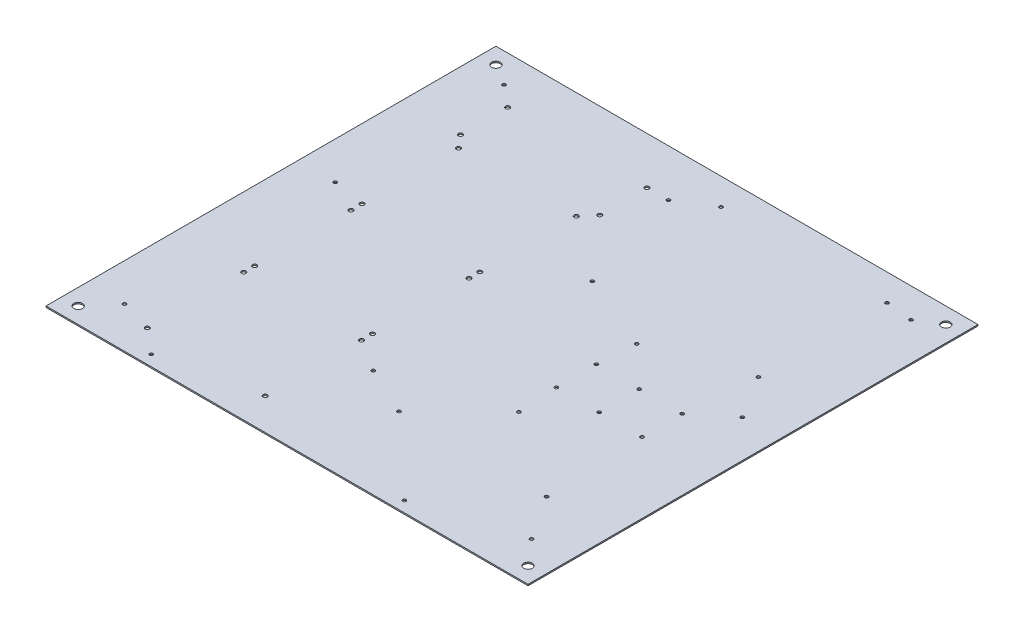
SolidWorks part; units mm, degrees
ref_plane "Front Plane" through (0, 0, 0) normal (0, 0, 1) x (1, 0, 0)
ref_plane "Top Plane" through (0, 0, 0) normal (0, 1, 0) x (1, 0, 0)
ref_plane "Right Plane" through (0, 0, 0) normal (1, 0, 0) x (0, 0, -1)
sketch "Sketch1" plane through (0, 0, 0) normal (0, 1, 0) x (1, 0, 0)
  line L1 (0, 0) -> (571.5, 0)
  line L2 (0, 0) -> (0, 533.4)
  line L3 (0, 533.4) -> (571.5, 533.4)
  line L4 (571.5, 0) -> (571.5, 533.4)
  dimension "D1" = 533.4
  dimension "D2" = 571.5
extrude "Boss-Extrude1" add sketch "Sketch1" along normal blind 1.5875
hole_wizard "#10-32 Tapped Hole1" positions "Sketch3" profile "Sketch2" tap size "#10-32" standard "ANSI Inch" end condition through all
sketch "Sketch3" plane through (0, 1.5875, 0) normal (0, 1, 0) x (1, 0, 0)
  line L0 (571.5, 533.4) -> (0, 533.4) construction
  line L1 (0, 533.4) -> (0, 0) construction
  point P0 (298.45, 501.65)
  point P2 (495.3, 501.65)
  point P4 (298.45, 349.25)
  point P6 (495.3, 349.25)
  dimension "D1" = 196.85
  dimension "D2" = 152.4
  dimension "D3" = 31.75
  dimension "D4" = 298.45
sketch "Sketch2" plane through (298.45, 1.5875, -501.65) normal (1, 0, 0) x (0, 0, 1)
  line L0 (0, 0) -> (0, 1.5875)
  line L1 (0, 1.5875) -> (2.0193, 1.5875)
  line L2 (2.0193, 1.5875) -> (2.0193, 0)
  line L5 (2.0193, 0) -> (0, 0)
  line L11 (0, -6.35) -> (0, 107.95) construction
  dimension "Thru Tap Drill Dia." = 4.0386
  dimension "Thru Tap Drill Depth" = 1.5875
cosmetic thread "Hole Thread1" parameters "D2"=4.826
cosmetic thread "Hole Thread2" parameters "D2"=4.826
cosmetic thread "Hole Thread3" parameters "D2"=4.826
cosmetic thread "Hole Thread4" parameters "D2"=4.826
hole_wizard "1/4-20 Tapped Hole1" positions "Sketch4" profile "Sketch5" tap size "1/4-20" standard "ANSI Inch" end condition through all
sketch "Sketch4" plane through (0, 1.5875, 0) normal (0, 1, 0) x (1, 0, 0)
  line L0 (571.5, 533.4) -> (0, 533.4) construction
  line L1 (0, 533.4) -> (0, 0) construction
  line L3 (69.85, 477.52) -> (234.95, 477.52) construction
  line L4 (69.85, 477.52) -> (69.85, 421.64) construction
  line L5 (69.85, 421.64) -> (234.95, 421.64) construction
  line L6 (234.95, 477.52) -> (234.95, 421.64) construction
  point P0 (82.55, 406.4)
  point P2 (82.55, 292.1)
  point P4 (222.25, 292.1)
  point P6 (222.25, 406.4)
  point P23 (82.55, 279.146)
  point P24 (82.55, 164.846)
  point P25 (222.25, 164.846)
  point P26 (222.25, 279.146)
  point P27 (82.55, 151.892)
  point P28 (82.55, 37.592)
  point P29 (222.25, 37.592)
  point P30 (222.25, 151.892)
  point P31 (69.85, 477.52)
  point P32 (234.95, 421.64)
  point P87 (69.85, 421.64)
  point P88 (234.95, 477.52)
  point P99 (152.4, 421.64)
  dimension "D1" = 114.3
  dimension "D2" = 139.7
  dimension "D3" = 127
  dimension "D4" = 82.55
  dimension "D6" = 12.954
  dimension "D7" = 165.1
  dimension "D8" = 55.88
  dimension "D9" = 152.4
  dimension "D10" = 15.24
  dimension "D5" = 3
sketch "Sketch5" plane through (82.55, 1.5875, -406.4) normal (1, 0, 0) x (0, 0, 1)
  line L0 (0, 0) -> (0, 1.5875)
  line L1 (0, 1.5875) -> (2.5527, 1.5875)
  line L2 (2.5527, 1.5875) -> (2.5527, 0)
  line L5 (2.5527, 0) -> (0, 0)
  line L11 (0, -6.35) -> (0, 107.95) construction
  dimension "Thru Tap Drill Dia." = 5.1054
  dimension "Thru Tap Drill Depth" = 1.5875
cosmetic thread "Hole Thread5" parameters "D2"=6.35
cosmetic thread "Hole Thread6" parameters "D2"=6.35
cosmetic thread "Hole Thread7" parameters "D2"=6.35
cosmetic thread "Hole Thread8" parameters "D2"=6.35
cosmetic thread "Hole Thread9" parameters "D2"=6.35
cosmetic thread "Hole Thread10" parameters "D2"=6.35
cosmetic thread "Hole Thread11" parameters "D2"=6.35
cosmetic thread "Hole Thread12" parameters "D2"=6.35
cosmetic thread "Hole Thread13" parameters "D2"=6.35
cosmetic thread "Hole Thread14" parameters "D2"=6.35
cosmetic thread "Hole Thread15" parameters "D2"=6.35
cosmetic thread "Hole Thread16" parameters "D2"=6.35
cosmetic thread "Hole Thread49" parameters "D2"=6.35
cosmetic thread "Hole Thread50" parameters "D2"=6.35
cosmetic thread "Hole Thread51" parameters "D2"=6.35
cosmetic thread "Hole Thread52" parameters "D2"=6.35
hole_wizard "#10-32 Tapped Hole2" positions "Sketch8" profile "Sketch9" tap size "#10-32" standard "ANSI Inch" end condition through all
sketch "Sketch8" plane through (0, 1.5875, 0) normal (0, 1, 0) x (1, 0, 0)
  line L0 (571.5, 0) -> (571.5, 533.4) construction
  line L1 (571.5, 533.4) -> (0, 533.4) construction
  point P0 (386.2, 266.324)
  point P2 (386.2, 218.826)
  point P22 (437, 266.324)
  point P23 (437, 218.826)
  point P24 (487.8, 266.324)
  point P25 (487.8, 218.826)
  dimension "D2" = 83.7
  dimension "D3" = 267.076
  dimension "D1" = 47.498
  dimension "D5" = 50.8
  dimension "D4" = 3
sketch "Sketch9" plane through (386.2, 1.5875, -266.324) normal (1, 0, 0) x (0, 0, 1)
  line L0 (0, 0) -> (0, 1.5875)
  line L1 (0, 1.5875) -> (2.0193, 1.5875)
  line L2 (2.0193, 1.5875) -> (2.0193, 0)
  line L5 (2.0193, 0) -> (0, 0)
  line L11 (0, -6.35) -> (0, 107.95) construction
  dimension "Thru Tap Drill Dia." = 4.0386
  dimension "Thru Tap Drill Depth" = 1.5875
cosmetic thread "Hole Thread29" parameters "D2"=4.826
cosmetic thread "Hole Thread30" parameters "D2"=4.826
cosmetic thread "Hole Thread31" parameters "D2"=4.826
cosmetic thread "Hole Thread32" parameters "D2"=4.826
cosmetic thread "Hole Thread33" parameters "D2"=4.826
cosmetic thread "Hole Thread34" parameters "D2"=4.826
hole_wizard "#10-32 Tapped Hole3" positions "Sketch10" profile "Sketch11" tap size "#10-32" standard "ANSI Inch" end condition through all
sketch "Sketch10" plane through (0, 1.5875, 0) normal (0, 1, 0) x (1, 0, 0)
  line L0 (0, 533.4) -> (0, 0) construction
  line L1 (0, 0) -> (571.5, 0) construction
  point P0 (317.5, 100.975)
  point P2 (492.506, 100.975)
  dimension "D1" = 175.006
  dimension "D2" = 100.975
  dimension "D3" = 317.5
sketch "Sketch11" plane through (317.5, 1.5875, -100.975) normal (1, 0, 0) x (0, 0, 1)
  line L0 (0, 0) -> (0, 1.5875)
  line L1 (0, 1.5875) -> (2.0193, 1.5875)
  line L2 (2.0193, 1.5875) -> (2.0193, 0)
  line L5 (2.0193, 0) -> (0, 0)
  line L11 (0, -6.35) -> (0, 107.95) construction
  dimension "Thru Tap Drill Dia." = 4.0386
  dimension "Thru Tap Drill Depth" = 1.5875
cosmetic thread "Hole Thread35" parameters "D2"=4.826
cosmetic thread "Hole Thread36" parameters "D2"=4.826
hole_wizard "3/8 Clearance Hole1" positions "Sketch12" profile "Sketch13" hole size "3/8" standard "ANSI Inch" end condition through all
sketch "Sketch12" plane through (0, 1.5875, 0) normal (0, 1, 0) x (1, 0, 0)
  line L0 (0, 266.7) -> (-33.6931, 266.7)
  line L1 (0, 533.4) -> (0, 0) construction
  line L3 (285.75, 533.4) -> (285.75, 552.2627)
  line L4 (571.5, 533.4) -> (0, 533.4) construction
  point P0 (19.05, 514.35)
  point P14 (552.45, 514.35)
  point P15 (552.45, 19.05)
  point P16 (19.05, 19.05)
  dimension "D1" = 495.3
  dimension "D2" = 533.4
sketch "Sketch13" plane through (19.05, 1.5875, -514.35) normal (1, 0, 0) x (0, 0, 1)
  line L0 (0, 0) -> (0, 1.5875)
  line L1 (0, 1.5875) -> (5.1587, 1.5875)
  line L2 (5.1587, 1.5875) -> (5.1587, 0)
  line L5 (5.1587, 0) -> (0, 0)
  line L11 (0, -6.35) -> (0, 107.95) construction
  dimension "Thru Hole Dia." = 10.3175
  dimension "Thru Hole Depth" = 1.5875
sketch "Sketch16" plane through (0, 1.5875, 0) normal (0, 1, 0) x (1, 0, 0)
  line L0 (527.05, 52.25) -> (527.05, 44.75)
  line L1 (527.05, 502.25) -> (527.05, 494.75)
  line L2 (527.05, 302.25) -> (527.05, 294.75)
  line L7 (47.7, 3.75) -> (47.7, 0)
  line L8 (47.7, 0) -> (55.0863, 0)
  line L9 (55.0863, 0) -> (55.0863, 533.4)
  line L10 (55.0863, 533.4) -> (33.8137, 533.4)
  line L11 (33.8137, 533.4) -> (33.8137, 0)
  line L12 (33.8137, 0) -> (41.2, 0)
  line L13 (41.2, 0) -> (41.2, 3.75)
  line L14 (47.7, 3.75) -> (47.7, 0)
  line L15 (47.7, 0) -> (55.0863, 0)
  line L16 (55.0863, 0) -> (55.0863, 533.4)
  line L17 (55.0863, 533.4) -> (33.8137, 533.4)
  line L18 (33.8137, 533.4) -> (33.8137, 0)
  line L19 (33.8137, 0) -> (41.2, 0)
  line L20 (41.2, 0) -> (41.2, 3.75)
  line L21 (530.3, 3.75) -> (530.3, 0)
  line L22 (530.3, 0) -> (537.6863, 0)
  line L23 (537.6863, 0) -> (537.6863, 533.4)
  line L24 (537.6863, 533.4) -> (516.4138, 533.4)
  line L25 (516.4138, 533.4) -> (516.4138, 0)
  line L26 (516.4138, 0) -> (523.8, 0)
  line L27 (523.8, 0) -> (523.8, 3.75)
  line L28 (530.3, 3.75) -> (530.3, 0)
  line L29 (530.3, 0) -> (537.6863, 0)
  line L30 (537.6863, 0) -> (537.6863, 533.4)
  line L31 (537.6863, 533.4) -> (516.4138, 533.4)
  line L32 (516.4138, 533.4) -> (516.4138, 0)
  line L33 (516.4138, 0) -> (523.8, 0)
  line L34 (523.8, 0) -> (523.8, 3.75)
  line L35 (510.6, 15.95) -> (514.35, 15.95)
  line L36 (514.35, 15.95) -> (514.35, 23.3362)
  line L37 (514.35, 23.3362) -> (57.15, 23.3362)
  line L38 (57.15, 23.3362) -> (57.15, 2.0637)
  line L39 (57.15, 2.0637) -> (514.35, 2.0637)
  line L40 (514.35, 2.0637) -> (514.35, 9.45)
  line L41 (514.35, 9.45) -> (510.6, 9.45)
  line L42 (510.6, 15.95) -> (514.35, 15.95)
  line L43 (514.35, 15.95) -> (514.35, 23.3362)
  line L44 (514.35, 23.3362) -> (57.15, 23.3362)
  line L45 (57.15, 23.3362) -> (57.15, 2.0637)
  line L46 (57.15, 2.0637) -> (514.35, 2.0637)
  line L47 (514.35, 2.0637) -> (514.35, 9.45)
  line L48 (514.35, 9.45) -> (510.6, 9.45)
  line L49 (510.6, 174.7) -> (514.35, 174.7)
  line L50 (514.35, 174.7) -> (514.35, 182.0862)
  line L51 (514.35, 182.0862) -> (273.05, 182.0862)
  line L52 (273.05, 182.0862) -> (273.05, 160.8137)
  line L53 (273.05, 160.8137) -> (514.35, 160.8137)
  line L54 (514.35, 160.8137) -> (514.35, 168.2)
  line L55 (514.35, 168.2) -> (510.6, 168.2)
  line L56 (510.6, 174.7) -> (514.35, 174.7)
  line L57 (514.35, 174.7) -> (514.35, 182.0862)
  line L58 (514.35, 182.0862) -> (273.05, 182.0862)
  line L59 (273.05, 182.0862) -> (273.05, 160.8137)
  line L60 (273.05, 160.8137) -> (514.35, 160.8137)
  line L61 (514.35, 160.8137) -> (514.35, 168.2)
  line L62 (514.35, 168.2) -> (510.6, 168.2)
  line L63 (44.45, 494.75) -> (44.45, 502.25)
  line L64 (44.45, 44.75) -> (44.45, 52.25)
  line L65 (44.45, 294.75) -> (44.45, 302.25)
  line L70 (510.6, 314.4) -> (514.35, 314.4)
  line L71 (514.35, 314.4) -> (514.35, 321.7862)
  line L72 (514.35, 321.7862) -> (273.05, 321.7862)
  line L73 (273.05, 321.7862) -> (273.05, 300.5137)
  line L74 (273.05, 300.5137) -> (514.35, 300.5137)
  line L75 (514.35, 300.5137) -> (514.35, 307.9)
  line L76 (514.35, 307.9) -> (510.6, 307.9)
  line L77 (510.6, 314.4) -> (514.35, 314.4)
  line L78 (514.35, 314.4) -> (514.35, 321.7862)
  line L79 (514.35, 321.7862) -> (273.05, 321.7862)
  line L80 (273.05, 321.7862) -> (273.05, 300.5137)
  line L81 (273.05, 300.5137) -> (514.35, 300.5137)
  line L82 (514.35, 300.5137) -> (514.35, 307.9)
  line L83 (514.35, 307.9) -> (510.6, 307.9)
  line L84 (263.6, 29.15) -> (263.6, 25.4)
  line L85 (263.6, 25.4) -> (270.9863, 25.4)
  line L86 (270.9863, 25.4) -> (270.9863, 533.4)
  line L87 (270.9863, 533.4) -> (249.7138, 533.4)
  line L88 (249.7138, 533.4) -> (249.7138, 25.4)
  line L89 (249.7138, 25.4) -> (257.1, 25.4)
  line L90 (257.1, 25.4) -> (257.1, 29.15)
  line L91 (263.6, 29.15) -> (263.6, 25.4)
  line L92 (263.6, 25.4) -> (270.9863, 25.4)
  line L93 (270.9863, 25.4) -> (270.9863, 533.4)
  line L94 (270.9863, 533.4) -> (249.7138, 533.4)
  line L95 (249.7138, 533.4) -> (249.7138, 25.4)
  line L96 (249.7138, 25.4) -> (257.1, 25.4)
  line L97 (257.1, 25.4) -> (257.1, 29.15)
  arc A1 (47.7, 3.75) -> (41.2, 3.75) centre (44.45, 3.75) ccw
  arc A2 (47.7, 3.75) -> (41.2, 3.75) centre (44.45, 3.75) ccw
  arc A3 (530.3, 3.75) -> (523.8, 3.75) centre (527.05, 3.75) ccw
  arc A4 (530.3, 3.75) -> (523.8, 3.75) centre (527.05, 3.75) ccw
  arc A5 (510.6, 15.95) -> (510.6, 9.45) centre (510.6, 12.7) ccw
  arc A6 (510.6, 15.95) -> (510.6, 9.45) centre (510.6, 12.7) ccw
  arc A7 (510.6, 174.7) -> (510.6, 168.2) centre (510.6, 171.45) ccw
  arc A8 (510.6, 174.7) -> (510.6, 168.2) centre (510.6, 171.45) ccw
  arc A10 (510.6, 314.4) -> (510.6, 307.9) centre (510.6, 311.15) ccw
  arc A11 (510.6, 314.4) -> (510.6, 307.9) centre (510.6, 311.15) ccw
  arc A12 (263.6, 29.15) -> (257.1, 29.15) centre (260.35, 29.15) ccw
  arc A13 (263.6, 29.15) -> (257.1, 29.15) centre (260.35, 29.15) ccw
  point P0 (44.45, 498.5)
  point P49 (44.45, 48.5)
  point P68 (44.45, 298.5)
  point P73 (527.05, 48.5)
  point P78 (527.05, 498.5)
  point P83 (527.05, 298.5)
  point P84 (260.35, 127.65)
  point P85 (260.35, 477.65)
  point P87 (389.1, 311.15)
  point P89 (389.1, 171.45)
  point P91 (412.1, 12.7)
  point P93 (112.1, 12.7)
  dimension "D1" = 0
  dimension "D2" = 0
  dimension "D3" = 0
  dimension "D4" = 0
  dimension "D5" = 0
  dimension "D6" = 0
hole_wizard "#10-32 Tapped Hole4" positions "Sketch16" profile "Sketch17" tap size "#10-32" standard "ANSI Inch" end condition up to next
sketch "Sketch17" plane through (44.45, 1.5875, -498.5) normal (1, 0, 0) x (0, 0, 1)
  line L0 (0, 0) -> (0, 1.5875)
  line L1 (0, 1.5875) -> (2.0193, 1.5875)
  line L2 (2.0193, 1.5875) -> (2.0193, 0)
  line L5 (2.0193, 0) -> (0, 0)
  line L11 (0, -6.35) -> (0, 107.95) construction
  dimension "Thru Tap Drill Dia." = 4.0386
  dimension "Thru Tap Drill Depth" = 1.5875
cosmetic thread "Hole Thread37" parameters "D2"=4.826
cosmetic thread "Hole Thread38" parameters "D2"=4.826
cosmetic thread "Hole Thread39" parameters "D2"=4.826
cosmetic thread "Hole Thread40" parameters "D2"=4.826
cosmetic thread "Hole Thread41" parameters "D2"=4.826
cosmetic thread "Hole Thread42" parameters "D2"=4.826
cosmetic thread "Hole Thread43" parameters "D2"=4.826
cosmetic thread "Hole Thread44" parameters "D2"=4.826
cosmetic thread "Hole Thread45" parameters "D2"=4.826
cosmetic thread "Hole Thread46" parameters "D2"=4.826
cosmetic thread "Hole Thread47" parameters "D2"=4.826
cosmetic thread "Hole Thread48" parameters "D2"=4.826
